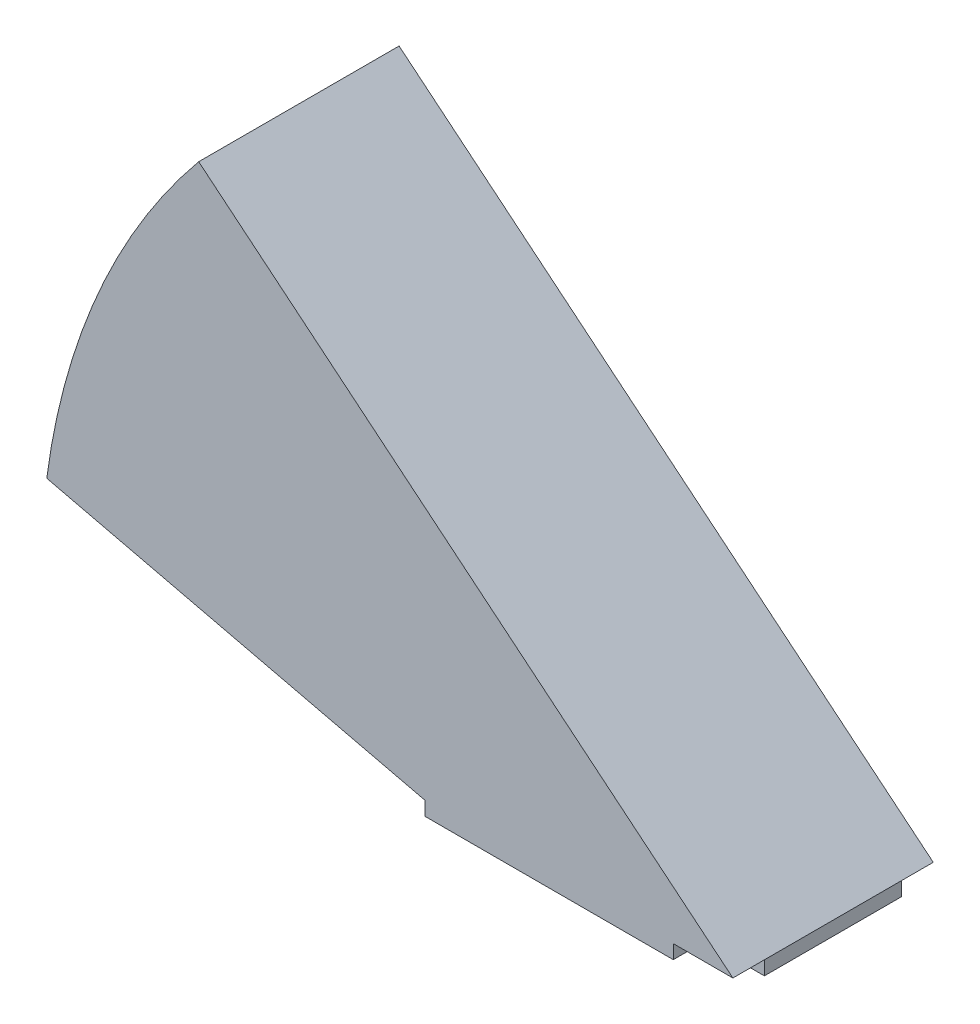
SolidWorks part; units mm, degrees
ref_plane "Front Plane" through (0, 0, 0) normal (0, 0, 1) x (1, 0, 0)
ref_plane "Top Plane" through (0, 0, 0) normal (0, 1, 0) x (1, 0, 0)
ref_plane "Right Plane" through (0, 0, 0) normal (1, 0, 0) x (0, 0, -1)
sketch "Sketch1" plane through (0, 0, 0) normal (0, 1, 0) x (1, 0, 0)
  line L0 (0, 28.75) -> (88.4, 28.75) construction
  line L1 (0, 0) -> (88.4, 0)
  line L2 (0, 0) -> (0, 57.5)
  line L3 (0, 57.5) -> (88.4, 57.5)
  line L4 (88.4, 0) -> (88.4, 57.5) construction
  line L5 (71.3, 48.45) -> (88.4, 48.45)
  line L6 (71.3, 9.05) -> (88.4, 9.05)
  line L7 (71.3, 9.05) -> (71.3, 48.45)
  line L8 (88.4, 48.45) -> (88.4, 57.5)
  line L9 (88.4, 9.05) -> (88.4, 0)
  line L10 (88.4, 48.45) -> (88.4, 9.05)
  line L11 (71.3, 9.05) -> (71.3, 0)
  line L12 (71.3, 48.45) -> (71.3, 57.5)
  circle A0 centre (31.9771, 49.7749) radius 4.5667
  circle A1 centre (31.9771, 7.7251) radius 4.5667
  point P8 (71.3, 28.75)
  point P18 (19.4468, 46.8537)
  point P19 (31.9771, 49.7749)
  dimension "D1" = 57.5
  dimension "D2" = 88.4
  dimension "D3" = 71.3
extrude "Boss-Extrude1" add sketch "Sketch1" along normal blind 4 contours L7 L12 L3 L2 L1 L11 | L10 L5 L7 L6
sketch "Sketch2" plane through (0, 0, 0) normal (0, 0, 1) x (1, 0, 0)
  line L0 (88.4, 4) -> (-64.8787, 130.2225)
  line L1 (-64.8787, 130.2225) -> (-64.8787, 4)
  line L2 (-64.8787, 4) -> (88.4, 4)
  line L3 (0, 4) -> (-108.4847, 29.7466)
  circle A0 centre (88.4, 4) radius 198.561
extrude "Boss-Extrude2" add sketch "Sketch2" against normal up to surface (57.5 mm away)
